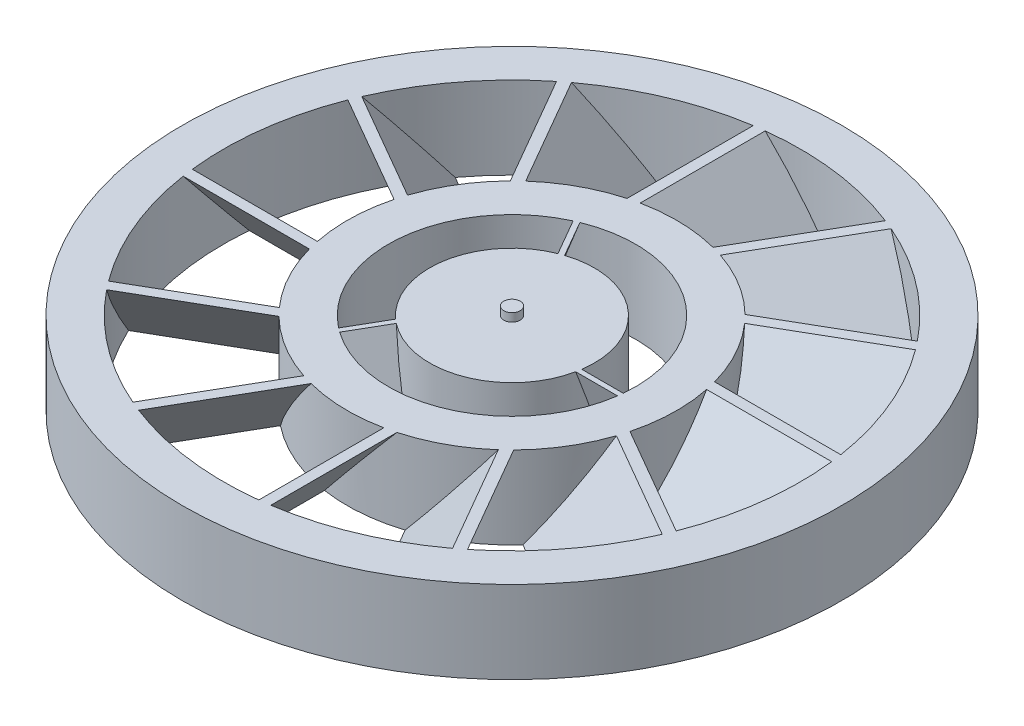
SolidWorks part; units mm, degrees
ref_plane "Front Plane" through (0, 0, 0) normal (0, 0, 1) x (1, 0, 0)
ref_plane "Top Plane" through (0, 0, 0) normal (0, 1, 0) x (1, 0, 0)
ref_plane "Right Plane" through (0, 0, 0) normal (1, 0, 0) x (0, 0, -1)
sketch "Sketch1" plane through (0, 0, 0) normal (0, 1, 0) x (1, 0, 0)
  circle A0 centre (0, 0) radius 20
  circle A1 centre (0, 0) radius 35
  circle A2 centre (0, 0) radius 40
  circle A3 centre (0, 0) radius 15
  circle A4 centre (0, 0) radius 10
  dimension "D1" = 40
  dimension "D2" = 70
  dimension "D3" = 80
  dimension "D4" = 20
  dimension "D5" = 30
extrude "Boss-Extrude1" add sketch "Sketch1" along normal blind 10 contours A4 | A0 A3 | A2 A1
sketch "Sketch2" plane through (0, 0, 0) normal (0, 0, 1) x (1, 0, 0)
  line L0 (0, 85.4193) -> (0, -73.7814) construction
sketch "Sketch3" plane through (0, 0, 0) normal (1, 0, 0) x (0, 0, -1)
  line L0 (-40, 0) -> (40, 0) construction
  line L1 (-35, 10) -> (-20, 10) construction
  line L2 (-35, 10) -> (-35, 0) construction
  line L3 (-35, 0) -> (-20, 0) construction
  line L4 (-20, 10) -> (-20, 0) construction
  line L5 (20, 10) -> (-20, 10) construction
  line L6 (-20, 10) -> (-20, 0) construction
sketch "Sketch4" plane through (0, 0, 0) normal (1, 0, 0) x (0, 0, -1)
  line L0 (-4.2624, 0) -> (4.0314, 10)
  line L1 (-40, 0) -> (40, 0) construction
  line L2 (40, 10) -> (-40, 10) construction
  line L3 (-2.9787, 0) -> (5.3151, 10)
  line L4 (5.3151, 10) -> (4.0314, 10)
  line L5 (-4.2624, 0) -> (-2.9787, 0)
extrude "Boss-Extrude2" add sketch "Sketch4" against normal up to surface and the other way up to surface from offset 30
pattern_circular "CirPattern1" count 12 over 360 about axis through (0, 0, 0) along (0, 1, 0) of "Boss-Extrude2"
sketch "Sketch5" plane through (0, 0, 0) normal (1, 0, 0) x (0, 0, -1)
  line L0 (-2.0524, 10) -> (1.4167, 0)
  line L1 (4.0314, 10) -> (-12.694, 10) construction
  line L2 (-40, 0) -> (40, 0) construction
  line L3 (2.1742, 0) -> (-1.4288, 10)
  line L4 (-1.4288, 10) -> (-2.0524, 10)
  line L5 (1.4167, 0) -> (2.1742, 0)
extrude "Boss-Extrude3" add sketch "Sketch5" along normal up to next from surface
pattern_circular "CirPattern3" count 3 over 360 about axis through (0, 0, 0) along (0, 1, 0) of "Boss-Extrude3"
sketch "Sketch6" plane through (0, 10, 0) normal (0, 1, 0) x (1, 0, 0)
  circle A0 centre (0, 0) radius 1
extrude "Boss-Extrude4" add sketch "Sketch6" along normal blind 1
equation "\"D4@Sketch1\"= \"D3@Sketch1\" * 2 / 8"
equation "\"D5@Sketch1\"= \"D3@Sketch1\" * 3 / 8"
equation "\"D1@Sketch1\"= \"D3@Sketch1\" / 2"
equation "\"D2@Sketch1\"= \"D3@Sketch1\" * 7 / 8"
